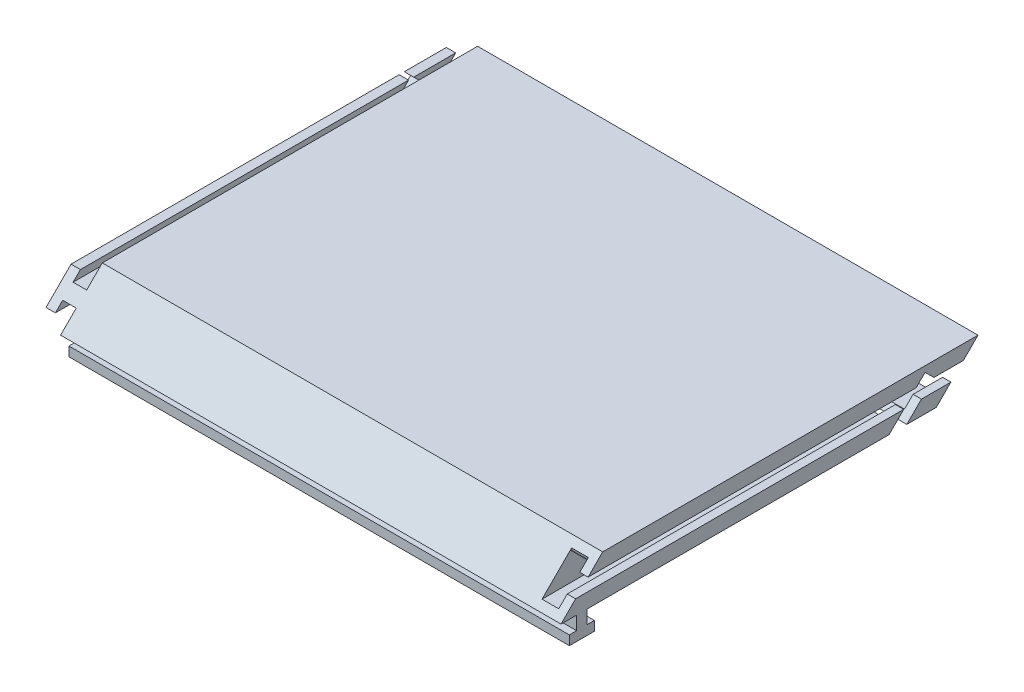
SolidWorks part; units mm, degrees
ref_plane "Front Plane" through (0, 0, 0) normal (0, 0, 1) x (1, 0, 0)
ref_plane "Top Plane" through (0, 0, 0) normal (0, 1, 0) x (1, 0, 0)
ref_plane "Right Plane" through (0, 0, 0) normal (1, 0, 0) x (0, 0, -1)
sketch "Sketch1" plane through (0, 0, 0) normal (0, 1, 0) x (1, 0, 0)
  line L1 (-120, -107.3415) -> (0, -107.3415)
  line L2 (-120, -107.3415) -> (-120, -7.3415)
  line L3 (-120, -7.3415) -> (0, -7.3415)
  line L4 (0, -107.3415) -> (0, -7.3415)
  dimension "D1" = 100
  dimension "D2" = 120
extrude "Boss-Extrude1" add sketch "Sketch1" along normal blind 10
sketch "Sketch2" plane through (0, 0, 7.3415) normal (0, 0, -1) x (-1, 0, 0)
  line L0 (0, 10) -> (0, 0) construction
  line L1 (0, 6.5) -> (6, 6.5)
  line L2 (0, 6.5) -> (0, 3.5)
  line L3 (0, 3.5) -> (6, 3.5)
  line L4 (6, 6.5) -> (6, 3.5)
  line L5 (0, 0) -> (120, 0) construction
  line L6 (0, 10) -> (120, 10) construction
  dimension "D1" = 6
  dimension "D2" = 0
  dimension "D3" = 3.5
  dimension "D4" = 3.5
extrude "Cut-Extrude1" cut sketch "Sketch2" against normal blind 120
sketch "Sketch3" plane through (0, 0, 7.3415) normal (0, 0, -1) x (-1, 0, 0)
  line L0 (6, 6.5) -> (0, 6.5) construction
  line L1 (6, 8.25) -> (3, 8.25)
  line L2 (6, 8.25) -> (6, 6.5)
  line L3 (6, 6.5) -> (3, 6.5)
  line L4 (3, 8.25) -> (3, 6.5)
  line L5 (6, 3.5) -> (6, 6.5) construction
  dimension "D1" = 1.75
  dimension "D2" = 0
  dimension "D3" = 0
  dimension "D4" = 3
extrude "Cut-Extrude2" cut sketch "Sketch3" against normal blind 120
sketch "Sketch4" plane through (0, 0, 7.3415) normal (0, 0, -1) x (-1, 0, 0)
  line L0 (0, 3.5) -> (6, 3.5) construction
  line L1 (3, 3.5) -> (6, 3.5)
  line L2 (3, 3.5) -> (3, 1.75)
  line L3 (3, 1.75) -> (6, 1.75)
  line L4 (6, 3.5) -> (6, 1.75)
  line L5 (6, 3.5) -> (6, 8.25) construction
  dimension "D1" = 0
  dimension "D2" = 0
  dimension "D3" = 1.75
  dimension "D4" = 3
extrude "Cut-Extrude3" cut sketch "Sketch4" against normal blind 120
sketch "Sketch5" plane through (-120, 0, 0) normal (-1, 0, 0) x (0, 0, 1)
  line L0 (7.3415, 10) -> (7.3415, 0) construction
  line L1 (7.3415, 6.5) -> (107.3415, 6.5)
  line L2 (7.3415, 6.5) -> (7.3415, 3.5)
  line L3 (7.3415, 3.5) -> (107.3415, 3.5)
  line L4 (107.3415, 6.5) -> (107.3415, 3.5)
  line L5 (107.3415, 10) -> (107.3415, 0) construction
  line L6 (7.3415, 0) -> (107.3415, 0) construction
  line L7 (7.3415, 10) -> (107.3415, 10) construction
  point P6 (7.3415, 5)
  point P9 (107.3415, 5)
  dimension "D1" = 0
  dimension "D2" = 0
  dimension "D3" = 3.5
  dimension "D4" = 3.5
extrude "Boss-Extrude2" add sketch "Sketch5" along normal blind 6
sketch "Sketch6" plane through (0, 3.5, 0) normal (0, -1, 0) x (-1, 0, 0)
  line L0 (126, -107.3415) -> (120, -107.3415) construction
  line L1 (126, -7.3415) -> (123, -7.3415)
  line L2 (126, -7.3415) -> (126, -107.3415)
  line L3 (126, -107.3415) -> (123, -107.3415)
  line L4 (123, -7.3415) -> (123, -107.3415)
extrude "Boss-Extrude3" add sketch "Sketch6" along normal blind 1.75
sketch "Sketch8" plane through (0, 6.5, 0) normal (0, 1, 0) x (1, 0, 0)
  line L0 (-126, -107.3415) -> (-120, -107.3415) construction
  line L1 (-126, -7.3415) -> (-123, -7.3415)
  line L2 (-126, -7.3415) -> (-126, -107.3415)
  line L3 (-126, -107.3415) -> (-123, -107.3415)
  line L4 (-123, -7.3415) -> (-123, -107.3415)
extrude "Boss-Extrude4" add sketch "Sketch8" along normal blind 1.75
sketch "Sketch9" plane through (0, 0, 0) normal (1, 0, 0) x (0, 0, -1)
  line L0 (-7.3415, 0) -> (-7.3415, 10)
  line L1 (-7.3415, 10) -> (-17.3415, 0)
  line L2 (-107.3415, 0) -> (-7.3415, 0) construction
  line L3 (-17.3415, 0) -> (-7.3415, 0)
extrude "Cut-Extrude4" cut sketch "Sketch9" against normal blind 140
sketch "Sketch10" plane through (0, 0, 0) normal (1, 0, 0) x (0, 0, -1)
  line L0 (-107.3415, 10) -> (-107.3415, 0)
  line L1 (-107.3415, 0) -> (-97.3415, 10)
  line L2 (-107.3415, 10) -> (-7.3415, 10) construction
  line L3 (-97.3415, 10) -> (-107.3415, 10)
extrude "Cut-Extrude5" cut sketch "Sketch10" against normal blind 140
sketch "Sketch11" plane through (0, 0, 0) normal (1, 0, 0) x (0, 0, -1)
  line L0 (-39.7159, -15.3033) -> (-19.7159, 4.6967)
  line L1 (-19.7159, 4.6967) -> (-23.2514, 8.2322)
  line L2 (-23.2514, 8.2322) -> (-43.2514, -11.7678)
  line L3 (-43.2514, -11.7678) -> (-39.7159, -15.3033)
  line L4 (-13.8415, 3.5) -> (-17.3415, 0) construction
  dimension "D1" = 5
  dimension "D2" = 5
  dimension "D3" = 12.5
  dimension "D4" = 20
sketch "Sketch12" plane through (0, 0, 0) normal (0, -1, 0) x (-1, 0, 0)
  line L0 (120, -17.3415) -> (120, -107.3415) construction
  line L1 (120, -103.8415) -> (0, -103.8415)
  line L2 (120, -103.8415) -> (120, -100.8415)
  line L3 (120, -100.8415) -> (0, -100.8415)
  line L4 (0, -103.8415) -> (0, -100.8415)
  line L5 (0, -107.3415) -> (0, -17.3415) construction
  line L6 (120, -107.3415) -> (0, -107.3415) construction
  dimension "D1" = 0
  dimension "D2" = 0
  dimension "D3" = 3
  dimension "D4" = 3.5
extrude "Boss-Extrude5" add sketch "Sketch12" along normal blind 6
sketch "Sketch13" plane through (0, 0, 100.8415) normal (0, 0, -1) x (-1, 0, 0)
  line L0 (0, -6) -> (0, 0) construction
  line L1 (120, -6) -> (0, -6)
  line L2 (120, -6) -> (120, -3)
  line L3 (120, -3) -> (0, -3)
  line L4 (0, -6) -> (0, -3)
extrude "Boss-Extrude6" add sketch "Sketch13" along normal blind 1.75
sketch "Sketch14" plane through (0, 0, 103.8415) normal (0, 0, 1) x (1, 0, 0)
  line L0 (0, -6) -> (-120, -6) construction
  line L1 (0, -6) -> (-120, -6)
  line L2 (0, -6) -> (0, -3)
  line L3 (0, -3) -> (-120, -3)
  line L4 (-120, -6) -> (-120, -3)
  line L5 (-120, -6) -> (-120, 0) construction
extrude "Boss-Extrude7" add sketch "Sketch14" along normal blind 1.75
sketch "Sketch15" plane through (0, 1.75, 0) normal (0, -1, 0) x (-1, 0, 0)
  line L1 (126, -105.5915) -> (122.0287, -105.5915)
  line L2 (126, -105.5915) -> (126, -5.3119)
  line L3 (126, -5.3119) -> (122.0287, -5.3119)
  line L4 (122.0287, -105.5915) -> (122.0287, -5.3119)
extrude "Cut-Extrude7" cut sketch "Sketch15" against normal blind 0.25
sketch "Sketch16" plane through (0, 8.25, 0) normal (0, 1, 0) x (1, 0, 0)
  line L1 (-126, -9.0915) -> (-122.0223, -9.0915)
  line L2 (-126, -9.0915) -> (-126, -109.2051)
  line L3 (-126, -109.2051) -> (-122.0223, -109.2051)
  line L4 (-122.0223, -9.0915) -> (-122.0223, -109.2051)
extrude "Cut-Extrude8" cut sketch "Sketch16" against normal blind 0.25
sketch "Sketch18" plane through (-126, 0, 0) normal (-1, 0, 0) x (0, 0, 1)
  line L1 (105.3415, 2) -> (5.949, 2)
  line L2 (105.3415, 2) -> (105.3415, 9.4594)
  line L3 (105.3415, 9.4594) -> (5.949, 9.4594)
  line L4 (5.949, 2) -> (5.949, 9.4594)
extrude "Cut-Extrude9" cut sketch "Sketch18" against normal blind 0.25
sketch "Sketch19" plane through (0, 6.5, 0) normal (0, 1, 0) x (1, 0, 0)
  line L1 (-120, -10.8415) -> (-123, -10.8415)
  line L2 (-120, -10.8415) -> (-120, -102.0999)
  line L3 (-120, -102.0999) -> (-123, -102.0999)
  line L4 (-123, -10.8415) -> (-123, -102.0999)
extrude "Cut-Extrude10" cut sketch "Sketch19" against normal blind 0.25
sketch "Sketch22" plane through (0, 3.5, 0) normal (0, -1, 0) x (-1, 0, 0)
  line L1 (120, -103.8415) -> (123, -103.8415)
  line L2 (120, -103.8415) -> (120, 1.7191)
  line L3 (120, 1.7191) -> (123, 1.7191)
  line L4 (123, -103.8415) -> (123, 1.7191)
extrude "Cut-Extrude11" cut sketch "Sketch22" against normal blind 0.25
sketch "Sketch23" plane through (-125.75, 0, 0) normal (-1, 0, 0) x (0, 0, 1)
  line L1 (9.3415, 8) -> (154.7586, 8)
  line L2 (9.3415, 8) -> (9.3415, -8.3762)
  line L3 (9.3415, -8.3762) -> (154.7586, -8.3762)
  line L4 (154.7586, 8) -> (154.7586, -8.3762)
extrude "Cut-Extrude12" cut sketch "Sketch23" against normal blind 0.25
sketch "Sketch24" plane through (-123, 0, 0) normal (1, 0, 0) x (0, 0, -1)
  line L1 (-105.3415, 2) -> (-13.2866, 2)
  line L2 (-105.3415, 2) -> (-105.3415, 3.75)
  line L3 (-105.3415, 3.75) -> (-13.2866, 3.75)
  line L4 (-13.2866, 2) -> (-13.2866, 3.75)
extrude "Cut-Extrude13" cut sketch "Sketch24" against normal blind 0.25
sketch "Sketch25" plane through (-123, 0, 0) normal (1, 0, 0) x (0, 0, -1)
  line L1 (-9.3415, 8) -> (-101.0915, 8)
  line L2 (-9.3415, 8) -> (-9.3415, 6.25)
  line L3 (-9.3415, 6.25) -> (-101.0915, 6.25)
  line L4 (-101.0915, 8) -> (-101.0915, 6.25)
extrude "Cut-Extrude14" cut sketch "Sketch25" against normal blind 0.25
sketch "Sketch27" plane through (0, -6, 0) normal (0, -1, 0) x (-1, 0, 0)
  line L1 (120, -105.5915) -> (-26.124, -105.5915)
  line L2 (120, -105.5915) -> (120, -94.6224)
  line L3 (120, -94.6224) -> (-26.124, -94.6224)
  line L4 (-26.124, -105.5915) -> (-26.124, -94.6224)
extrude "Cut-Extrude15" cut sketch "Sketch27" against normal blind 0.25
sketch "Sketch28" plane through (0, 0, 105.5915) normal (0, 0, 1) x (1, 0, 0)
  line L1 (0, -3) -> (-131.9104, -3)
  line L2 (0, -3) -> (0, -12.7021)
  line L3 (0, -12.7021) -> (-131.9104, -12.7021)
  line L4 (-131.9104, -3) -> (-131.9104, -12.7021)
extrude "Cut-Extrude16" cut sketch "Sketch28" against normal blind 0.25
sketch "Sketch29" plane through (0, 0, 99.0915) normal (0, 0, -1) x (-1, 0, 0)
  line L1 (120, -3) -> (-27.0622, -3)
  line L2 (120, -3) -> (120, -28.7384)
  line L3 (120, -28.7384) -> (-27.0622, -28.7384)
  line L4 (-27.0622, -3) -> (-27.0622, -28.7384)
extrude "Cut-Extrude17" cut sketch "Sketch29" against normal blind 0.25
sketch "Sketch30" plane through (0, 0, 100.8415) normal (0, 0, -1) x (-1, 0, 0)
  line L0 (120, 0) -> (0, 0) construction
  line L1 (120, 0) -> (0, 0)
  line L2 (120, 0) -> (120, -3)
  line L3 (120, -3) -> (0, -3)
  line L4 (0, 0) -> (0, -3)
  line L5 (120, -3) -> (0, -3) construction
extrude "Cut-Extrude18" cut sketch "Sketch30" against normal blind 0.25
sketch "Sketch31" plane through (0, 0, 103.8415) normal (0, 0, 1) x (1, 0, 0)
  line L1 (0, 0) -> (-120, 0)
  line L2 (0, 0) -> (0, -3)
  line L3 (0, -3) -> (-120, -3)
  line L4 (-120, 0) -> (-120, -3)
extrude "Cut-Extrude19" cut sketch "Sketch31" against normal blind 0.25
sketch "Sketch32" plane through (0, -3, 0) normal (0, 1, 0) x (1, 0, 0)
  line L1 (-120, -105.3415) -> (0, -105.3415)
  line L2 (-120, -105.3415) -> (-120, -103.5915)
  line L3 (-120, -103.5915) -> (0, -103.5915)
  line L4 (0, -105.3415) -> (0, -103.5915)
extrude "Cut-Extrude20" cut sketch "Sketch32" against normal blind 0.25
sketch "Sketch33" plane through (0, -3, 0) normal (0, 1, 0) x (1, 0, 0)
  line L1 (0, -101.0915) -> (-120, -101.0915)
  line L2 (0, -101.0915) -> (0, -99.3415)
  line L3 (0, -99.3415) -> (-120, -99.3415)
  line L4 (-120, -101.0915) -> (-120, -99.3415)
extrude "Cut-Extrude21" cut sketch "Sketch33" against normal blind 0.25
sketch "Sketch36" plane through (-3, 0, 0) normal (-1, 0, 0) x (0, 0, 1)
  line L1 (105.5915, 1.75) -> (9.0915, 1.75)
  line L2 (105.5915, 1.75) -> (105.5915, 8.25)
  line L3 (105.5915, 8.25) -> (9.0915, 8.25)
  line L4 (9.0915, 1.75) -> (9.0915, 8.25)
extrude "Cut-Extrude23" cut sketch "Sketch36" against normal blind 0.5
sketch "Sketch39" plane through (-2.5, 0, 0) normal (-1, 0, 0) x (0, 0, 1)
  line L1 (9.0915, 8.25) -> (105.5915, 8.25)
  line L2 (9.0915, 8.25) -> (9.0915, 1.75)
  line L3 (9.0915, 1.75) -> (105.5915, 1.75)
  line L4 (105.5915, 8.25) -> (105.5915, 1.75)
extrude "Cut-Extrude27" cut sketch "Sketch39" against normal blind 0.5
sketch "Sketch41" plane through (0, 1.75, 0) normal (0, 1, 0) x (1, 0, 0)
  line L1 (-6, -15.5915) -> (-2, -15.5915)
  line L2 (-6, -15.5915) -> (-6, -107.2951)
  line L3 (-6, -107.2951) -> (-2, -107.2951)
  line L4 (-2, -15.5915) -> (-2, -107.2951)
extrude "Cut-Extrude28" cut sketch "Sketch41" against normal blind 0.3
sketch "Sketch42" plane through (0, 8.25, 0) normal (0, -1, 0) x (-1, 0, 0)
  line L1 (5.9875, -99.058) -> (2, -99.058)
  line L2 (5.9875, -99.058) -> (5.9875, -6.8878)
  line L3 (5.9875, -6.8878) -> (2, -6.8878)
  line L4 (2, -99.058) -> (2, -6.8878)
extrude "Cut-Extrude29" cut sketch "Sketch42" against normal blind 0.3
sketch "Sketch43" plane through (0, 0, 0) normal (1, 0, 0) x (0, 0, -1)
  line L0 (-19.3268, 7.9142) -> (-33.4689, -6.2279)
  line L1 (-33.4689, -6.2279) -> (-32.0547, -7.6421)
  line L2 (-32.0547, -7.6421) -> (-17.9126, 6.5)
  line L3 (-17.9126, 6.5) -> (-19.3268, 7.9142)
  line L4 (-13.8415, 3.5) -> (-17.3415, 0) construction
  dimension "D1" = 2
  dimension "D2" = 20
  dimension "D3" = 5
  dimension "D4" = 5
extrude "Cut-Extrude30" cut sketch "Sketch43" against normal blind 150
sketch "Sketch44" plane through (0, -5.75, 0) normal (0, -1, 0) x (-1, 0, 0)
  line L1 (120, -105.3415) -> (0, -105.3415)
  line L2 (120, -105.3415) -> (120, -99.3415)
  line L3 (120, -99.3415) -> (0, -99.3415)
  line L4 (0, -105.3415) -> (0, -99.3415)
extrude "Cut-Extrude31" cut sketch "Sketch44" against normal blind 0.25
sketch "Sketch45" plane through (0, 0, 0) normal (1, 0, 0) x (0, 0, -1)
  line L0 (-19.3268, 7.9142) -> (-20.0339, 8.6213)
  line L1 (-20.0339, 8.6213) -> (-29.4878, -0.8326)
  line L2 (-29.4878, -0.8326) -> (-28.7807, -1.5397)
  line L3 (-28.7807, -1.5397) -> (-19.3268, 7.9142)
  dimension "D1" = 1
extrude "Cut-Extrude32" cut sketch "Sketch45" against normal blind 150
